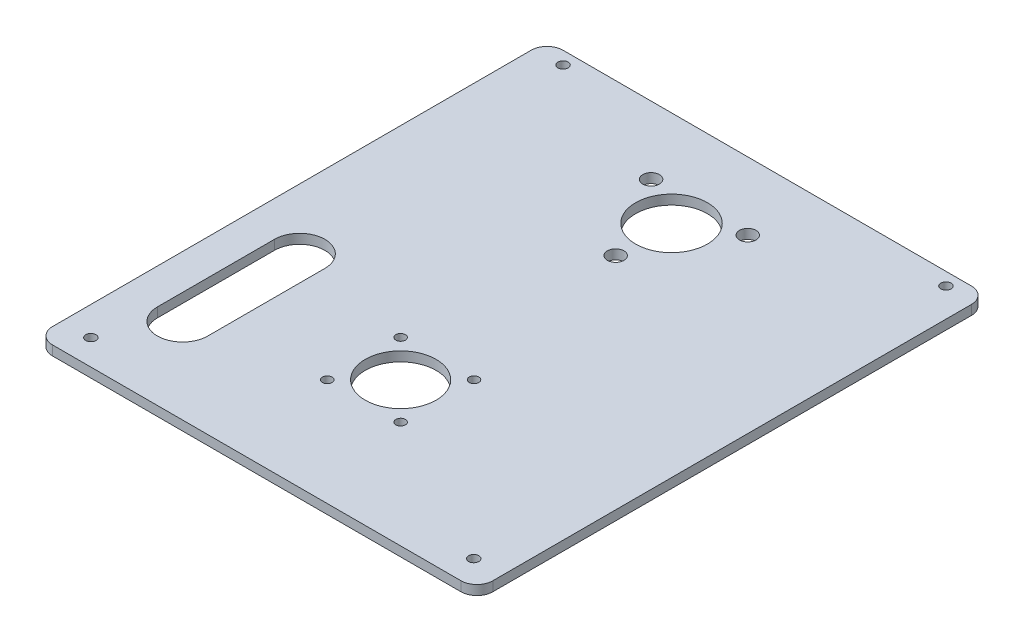
SolidWorks part; units mm, degrees
ref_plane "前视基准面" through (0, 0, 0) normal (0, 0, 1) x (1, 0, 0)
ref_plane "上视基准面" through (0, 0, 0) normal (0, 1, 0) x (1, 0, 0)
ref_plane "右视基准面" through (0, 0, 0) normal (1, 0, 0) x (0, 0, -1)
other "Configuration Table"
sketch "草图1" plane through (0, 0, 0) normal (0, 1, 0) x (1, 0, 0)
  line L0 (0, 106.9974) -> (0, -129.851) construction
  line L13 (64, -80) -> (-64, -80)
  line L14 (69, -75) -> (69, 75)
  line L15 (64, 80) -> (-64, 80)
  line L16 (-69, -75) -> (-69, 75)
  line L17 (69, -80) -> (-69, 80) construction
  line L18 (69, 80) -> (-69, -80) construction
  line L19 (-119.1376, 0) -> (183.6105, 0) construction
  line L20 (-50, -16.55) -> (-50, -53.25) construction
  line L25 (-42.1, -16.55) -> (-42.1, -53.25)
  line L26 (-57.9, -16.55) -> (-57.9, -53.25)
  arc A16 (69, -75) -> (64, -80) centre (64, -75) cw
  arc A17 (-64, -80) -> (-69, -75) centre (-64, -75) cw
  arc A18 (-69, 75) -> (-64, 80) centre (-64, 75) cw
  arc A19 (69, 75) -> (64, 80) centre (64, 75) ccw
  circle A20 centre (60, 76) radius 1.6
  circle A21 centre (-60, 76) radius 1.6
  circle A24 centre (0, -34.9) radius 11.1
  circle A25 centre (11.5, -46.4) radius 1.5
  circle A26 centre (11.5, -23.4) radius 1.5
  circle A27 centre (-11.5, -46.4) radius 1.5
  circle A28 centre (-11.5, -23.4) radius 1.5
  circle A29 centre (0, 50) radius 11.25
  circle A31 centre (60, -72) radius 1.6
  circle A32 centre (-60, -72) radius 1.6
  circle A33 centre (0, 32.5) radius 2.6
  circle A34 centre (15.15, 58.75) radius 2.6
  circle A35 centre (-15.15, 58.75) radius 2.6
  arc A40 (-42.1, -16.55) -> (-57.9, -16.55) centre (-50, -16.55) ccw
  arc A41 (-57.9, -53.25) -> (-42.1, -53.25) centre (-50, -53.25) ccw
  point P0 (0, 0)
  point P50 (-50, -34.9)
  point P55 (-50, -8.65)
  point P56 (-50, -61.15)
  dimension "D3" = 5
  dimension "D4" = 9
  dimension "D5" = 3.2
  dimension "D7" = 34.9
  dimension "D10" = 11.5
  dimension "D12" = 23.4
  dimension "D13" = 11.5
  dimension "D16" = 22.5
  dimension "D17" = 8
  dimension "D18" = 3.2
  dimension "D8" = 22.2
  dimension "D11" = 3
  dimension "D14" = 3
  dimension "D15" = 50
  dimension "D21" = 5.2
  dimension "D24" = 5.2
  dimension "D1" = 138
  dimension "D2" = 160
  dimension "D6" = 9
  dimension "D9" = 46.4
  dimension "D19" = 148
  dimension "D20" = 32.5
  dimension "D22" = 58.75
  dimension "D23" = 15.15
  dimension "D25" = 52.5
  dimension "D26" = 15.8
  dimension "D27" = 50
  dimension "D28" = 34.9
extrude "凸台-拉伸1" add sketch "草图1" along normal blind 3
